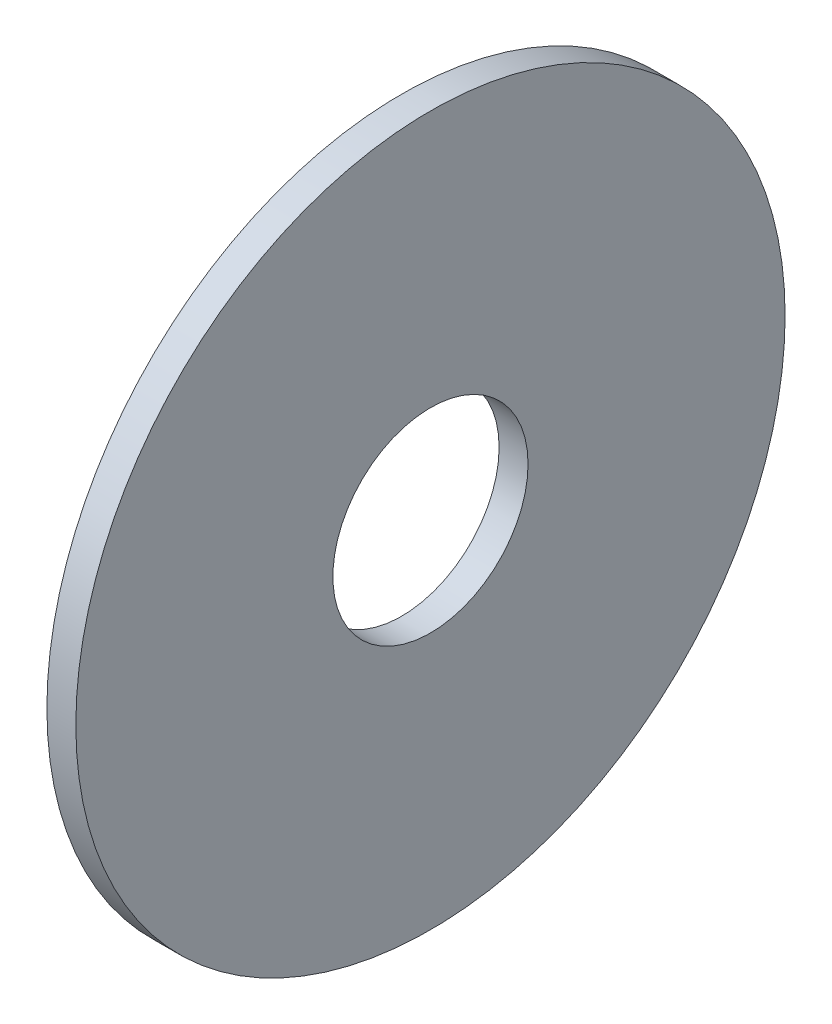
SolidWorks part; units mm, degrees
ref_plane "Front Plane" through (0, 0, 0) normal (0, 0, 1) x (1, 0, 0)
ref_plane "Top Plane" through (0, 0, 0) normal (0, 1, 0) x (1, 0, 0)
ref_plane "Right Plane" through (0, 0, 0) normal (1, 0, 0) x (0, 0, -1)
sketch "Sketch1" plane through (0, 0, 0) normal (1, 0, 0) x (0, 0, -1)
  circle A0 centre (0, 0) radius 15.875
  circle A1 centre (0, 0) radius 4.3688
  dimension "OD" = 31.75
  dimension "ID" = 8.7376
extrude "Boss-Extrude1" add sketch "Sketch1" along normal blind 1.2954
